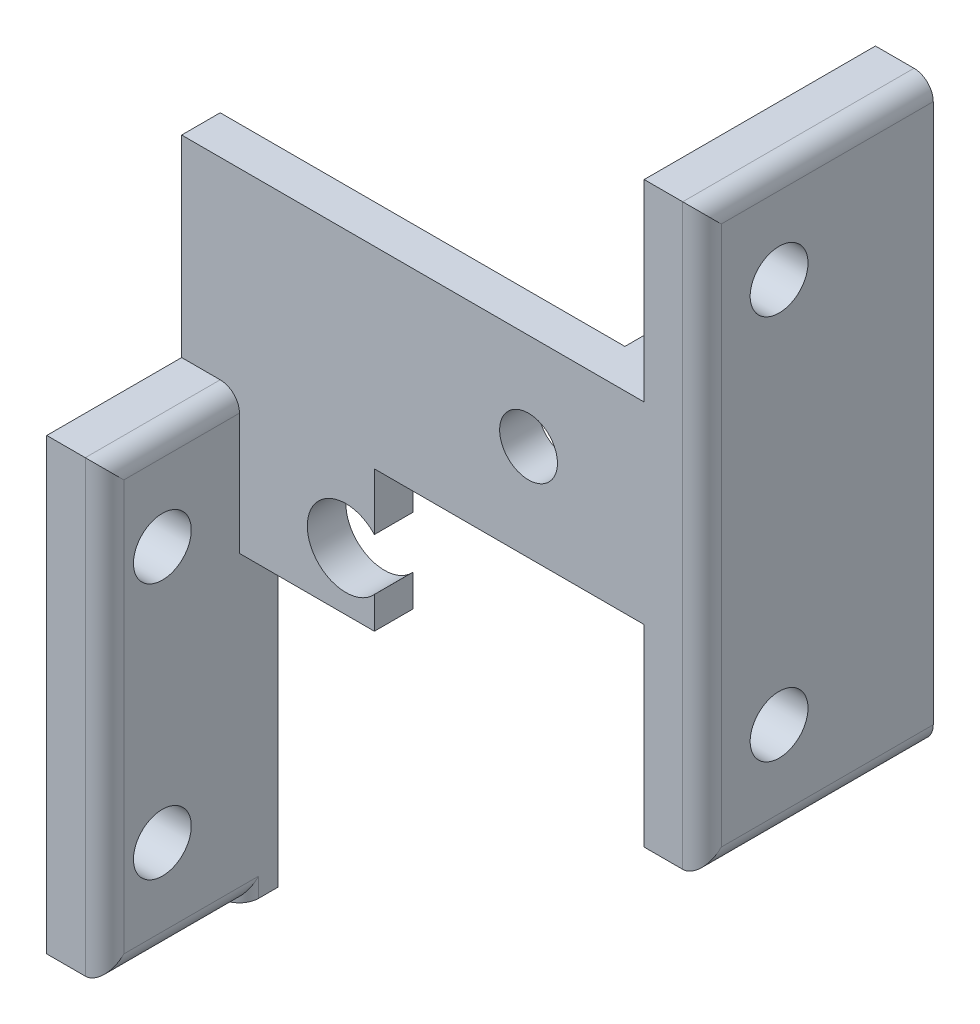
SolidWorks part; units mm, degrees
ref_plane "Alzado" through (0, 0, 0) normal (0, 0, 1) x (1, 0, 0)
ref_plane "Planta" through (0, 0, 0) normal (0, 1, 0) x (1, 0, 0)
ref_plane "Vista lateral" through (0, 0, 0) normal (1, 0, 0) x (0, 0, -1)
sketch "Croquis1" plane through (0, 0, 0) normal (1, 0, 0) x (0, 0, -1)
  line L1 (-24, 0) -> (0, 0)
  line L2 (-24, 0) -> (-24, -33.3)
  line L3 (-24, -33.3) -> (0, -33.3)
  line L4 (0, 0) -> (0, -33.3)
  dimension "D1" = 33.3
  dimension "D2" = 24
extrude "Saliente-Extruir2" add sketch "Croquis1" along normal blind 7
sketch "Croquis3" plane through (0, 0, 0) normal (0, 1, 0) x (1, 0, 0)
  line L0 (7, 0) -> (7, -24) construction
  line L1 (7, -3) -> (3, -3)
  line L2 (7, -3) -> (7, -22)
  line L3 (7, -22) -> (3, -22)
  line L4 (3, -3) -> (3, -22)
  line L5 (7, 0) -> (0, 0) construction
  line L6 (7, -24) -> (0, -24) construction
  line L7 (0, 0) -> (0, -24) construction
  dimension "D1" = 3
  dimension "D2" = 2
  dimension "D3" = 3
extrude "Cortar-Extruir1" cut sketch "Croquis3" against normal through all
sketch "Croquis7" plane through (0, 0, 0) normal (-1, 0, 0) x (0, 0, 1)
  line L0 (24, -33.3) -> (0, -33.3) construction
  line L1 (-7, 15) -> (31, 15)
  line L2 (-7, 15) -> (-7, -44.3)
  line L3 (-7, -44.3) -> (31, -44.3)
  line L4 (31, 15) -> (31, -44.3)
  line L5 (0, 0) -> (24, 0) construction
  line L6 (24, 0) -> (24, -33.3) construction
  line L7 (0, -33.3) -> (0, 0) construction
  line L9 (-7, 15) -> (0, 15)
  line L10 (-7, 15) -> (-7, 0)
  line L11 (-7, 0) -> (0, 0)
  line L12 (0, 15) -> (0, 0)
  line L13 (24, 0) -> (31, 0)
  line L14 (24, 0) -> (24, 15)
  line L15 (24, 15) -> (31, 15)
  line L16 (31, 0) -> (31, 15)
  line L17 (24, -33.3) -> (31, -33.3)
  line L18 (24, -33.3) -> (24, -44.3)
  line L19 (24, -44.3) -> (31, -44.3)
  line L20 (31, -33.3) -> (31, -44.3)
  line L21 (0, -33.3) -> (-7, -33.3)
  line L22 (0, -33.3) -> (0, -44.3)
  line L23 (0, -44.3) -> (-7, -44.3)
  line L24 (-7, -33.3) -> (-7, -44.3)
  circle A0 centre (-4, -15) radius 1.5
  circle A1 centre (-4, -28.3) radius 1.5
  circle A2 centre (28, -28.3) radius 1.5
  circle A3 centre (28, -15) radius 1.5
  circle A4 centre (4, 11) radius 1.5
  circle A5 centre (20, 11) radius 1.5
  circle A6 centre (4, -40.3) radius 1.5
  circle A7 centre (20, -40.3) radius 1.5
  dimension "D6" = 15
  dimension "D7" = 3
  dimension "D9" = 3
  dimension "D10" = 5
  dimension "D12" = 4
  dimension "D13" = 4
  dimension "D14" = 3
  dimension "D15" = 4
  dimension "D16" = 4
  dimension "D17" = 3
  dimension "D18" = 5
  dimension "D19" = 3
  dimension "D20" = 3
  dimension "D21" = 3
  dimension "D22" = 15
  dimension "D23" = 3
  dimension "D24" = 3
  dimension "D25" = 4
  dimension "D26" = 4
  dimension "D27" = 4
  dimension "D28" = 4
  dimension "D5" = 3
  dimension "D8" = 3
  dimension "D11" = 3
  dimension "D1" = 11
  dimension "D2" = 15
  dimension "D3" = 7
  dimension "D4" = 7
extrude "Saliente-Extruir3" add sketch "Croquis7" along normal blind 3 separate body
sketch "Croquis8" plane through (0, 0, 24) normal (0, 0, 1) x (1, 0, 0)
  line L1 (0, 0) -> (18, 0)
  line L2 (0, 0) -> (0, -10)
  line L3 (0, -10) -> (18, -10)
  line L4 (18, 0) -> (18, -10)
  circle A1 centre (15, -5) radius 1.5
  circle A2 centre (3, -5) radius 1.5
  dimension "D3" = 12
  dimension "D2" = 3
  dimension "D5" = 3
  dimension "D6" = 5
  dimension "D4" = 3
  dimension "D7" = 5
  dimension "D1" = 10
  dimension "D8" = 3
extrude "Saliente-Extruir5" add sketch "Croquis8" against normal blind 2
sketch "Croquis9" plane through (0, 0, 0) normal (0, 0, -1) x (-1, 0, 0)
  line L1 (0, 0) -> (-18, 0)
  line L2 (0, 0) -> (0, -10)
  line L3 (0, -10) -> (-18, -10)
  line L4 (-18, 0) -> (-18, -10)
  circle A1 centre (-15, -5) radius 1.5
  dimension "D1" = 3
extrude "Saliente-Extruir6" add sketch "Croquis9" against normal blind 3
sketch "Croquis10" plane through (18, 0, 0) normal (1, 0, 0) x (0, 0, -1)
  line L1 (-24, 0) -> (0, 0)
  line L2 (-24, 0) -> (-24, -10)
  line L3 (-24, -10) -> (0, -10)
  line L4 (0, 0) -> (0, -10)
extrude "Saliente-Extruir7" add sketch "Croquis10" along normal blind 3
sketch "Croquis11" plane through (3, 0, 0) normal (1, 0, 0) x (0, 0, -1)
  line L0 (-22, -33.3) -> (-22, 0) construction
  line L1 (-22, 0) -> (-3, 0)
  line L2 (-22, 0) -> (-22, -38)
  line L3 (-22, -38) -> (-3, -38)
  line L4 (-3, 0) -> (-3, -38)
  dimension "D1" = 38
  dimension "D2" = 19
extrude "Cortar-Extruir5" cut sketch "Croquis11" against normal through all
sketch "Croquis14" plane through (0, 0, 24) normal (0, 0, 1) x (1, 0, 0)
  line L0 (0, -38.8) -> (0, -33.3) construction
  line L1 (0, -33.3) -> (0, -44.3) construction
  line L2 (0, 0) -> (0, -33.3) construction
  line L3 (7, -10) -> (7, -33.3) construction
  line L4 (7, -17.3) -> (0, -17.3)
  line L5 (7, -17.3) -> (7, -33.3)
  line L6 (7, -33.3) -> (0, -33.3)
  line L7 (0, -17.3) -> (0, -33.3)
  line L8 (0, -33.3) -> (7, -33.3) construction
  line L9 (7, -33.3) -> (0, -33.3) construction
  dimension "D1" = 16
  dimension "D2" = 16
  dimension "D3" = 0
extrude "Cortar-Extruir7" cut sketch "Croquis14" against normal blind 2
sketch "Croquis15" plane through (0, 0, 0) normal (1, 0, 0) x (0, 0, -1)
  line L0 (-31, 0) -> (-31, -33.3) construction
  line L1 (-31, 0) -> (-24, 0)
  line L2 (-31, 0) -> (-31, -10)
  line L3 (-31, -10) -> (-24, -10)
  line L4 (-24, 0) -> (-24, -10)
  line L5 (7, 0) -> (0, 0)
  line L6 (7, 0) -> (7, -10)
  line L7 (7, -10) -> (0, -10)
  line L8 (0, 0) -> (0, -10)
extrude "Cortar-Extruir8" cut sketch "Croquis15" against normal through all
sketch "Croquis17" plane through (21, 0, 0) normal (1, 0, 0) x (0, 0, -1)
  line L0 (0, -33.3) -> (0, -10) construction
  line L1 (-24, -10) -> (0, -10)
  line L2 (-24, -10) -> (-24, -20)
  line L3 (-24, -20) -> (0, -20)
  line L4 (0, -10) -> (0, -20)
  line L6 (-24, -10) -> (0, -10)
  line L7 (-24, -10) -> (-24, 10)
  line L8 (-24, 10) -> (0, 10)
  line L9 (0, -10) -> (0, 10)
  circle A0 centre (-20, 5) radius 1.5
  circle A1 centre (-4, 5) radius 1.5
  circle A2 centre (-20, -15) radius 1.5
  circle A3 centre (-4, -15) radius 1.5
  line M7 (-24, 0) -> (-24, -10)
  line M8 (-24, -10) -> (0, -10)
  line M9 (0, -10) -> (0, 0)
  line M10 (0, 0) -> (-24, 0)
  dimension "D3" = 3
  dimension "D4" = 3
  dimension "D5" = 5
  dimension "D6" = 4
  dimension "D7" = 5
  dimension "D8" = 4
  dimension "D9" = 3
  dimension "D10" = 3
  dimension "D11" = 4
  dimension "D12" = 4
  dimension "D13" = 5
  dimension "D14" = 5
  dimension "D1" = 20
  dimension "D2" = 10
extrude "Saliente-Extruir8" add sketch "Croquis17" along normal blind 3 contours L4 L2 L3 A3 A2 M8 | M10 M7 M8 M9 | L9 L8 L7 A1 A0 M10
fillet "Redondeo2" radius 1 16 edges at (0, -38.8, 24) (0, -44.3, 12) (0, -10, 27.5) (0, -33.3, 27.5) (0, -21.65, 31) (7, -33.3, 1.5) (0, -33.3, -3.5) (0, -10, -3.5) (0, -21.65, -7) (7, -21.65, 0) (24, 10, 12) (24, -5, 0) (24, -20, 12) (24, -5, 24)
sketch "Croquis18" plane through (0, -44.3, 0) normal (0, -1, 0) x (-1, 0, 0)
  line L0 (3, -12) -> (-28.724, -12) construction
  line L1 (3, 0) -> (3, -24) construction
  line L2 (3, 7) -> (1, 7) construction
  line L3 (3, -12) -> (-24, -12)
  line L4 (3, -12) -> (3, 7)
  line L5 (3, 7) -> (-24, 7)
  line L6 (-24, -12) -> (-24, 7)
  line L7 (-24, -23) -> (-24, -1) construction
  dimension "D1" = 0
  dimension "D2" = 0
extrude "Cortar-Extruir9" cut sketch "Croquis18" against normal through all
sketch "Croquis19" plane through (0, 0, 24) normal (0, 0, 1) x (1, 0, 0)
  line L0 (7, -17.3) -> (0, -17.3) construction
  line L1 (7, -10) -> (7, -17.3) construction
  circle A0 centre (5.52, -14.3) radius 2
  dimension "D1" = 4
  dimension "D2" = 3
  dimension "D3" = 1.48
extrude "Cortar-Extruir10" cut sketch "Croquis19" against normal blind 10
sketch "Croquis20" plane through (0, 0, 0) normal (1, 0, 0) x (0, 0, -1)
  line L1 (-24, -33.3) -> (-12, -33.3)
  line L2 (-24, -33.3) -> (-24, -44.3)
  line L3 (-24, -44.3) -> (-12, -44.3)
  line L4 (-12, -33.3) -> (-12, -44.3)
extrude "Cortar-Extruir11" cut sketch "Croquis20" against normal through all
